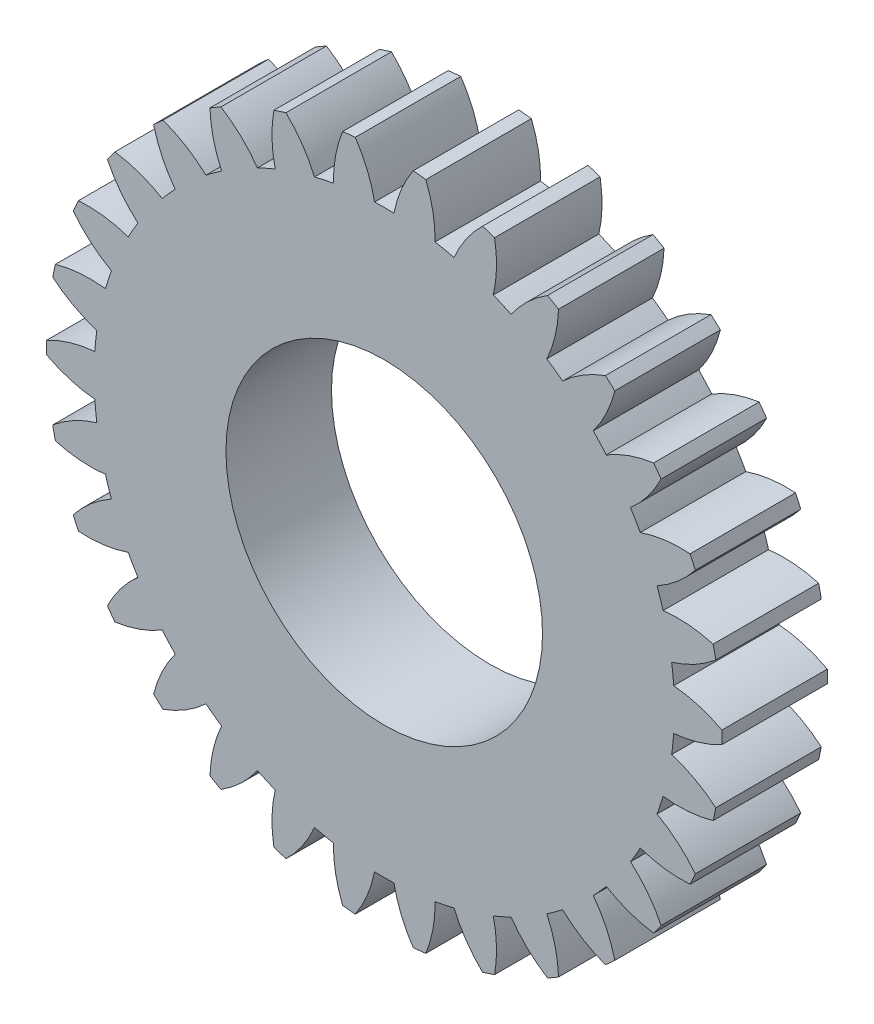
SolidWorks part; units mm, degrees
ref_plane "前基準面" through (0, 0, 0) normal (0, 0, 1) x (1, 0, 0)
ref_plane "上基準面" through (0, 0, 0) normal (0, 1, 0) x (1, 0, 0)
ref_plane "右基準面" through (0, 0, 0) normal (1, 0, 0) x (0, 0, -1)
sketch "草圖1" plane through (0, 0, 0) normal (0, 0, 1) x (1, 0, 0)
  circle A0 centre (0, 0) radius 15
  arc A240 (-31.9943, -0.6021) -> (-27.4291, -1.9593) centre (-26.3602, 9.993) ccw
  arc A241 (-27.4291, -1.9593) -> (-27.2371, -3.7863) centre (0, 0) ccw
  arc A242 (-27.2371, -3.7863) -> (-31.4204, -6.063) centre (-23.7065, -15.2552) ccw
  arc A243 (-31.4204, -6.063) -> (-31.17, -7.241) centre (0, 0) ccw
  arc A244 (-31.17, -7.241) -> (-26.4224, -7.6193) centre (-27.8618, 4.294) ccw
  arc A245 (-26.4224, -7.6193) -> (-25.8547, -9.3665) centre (0, 0) ccw
  arc A246 (-25.8547, -9.3665) -> (-29.4732, -12.4632) centre (-20.0167, -19.8507) ccw
  arc A247 (-29.4732, -12.4632) -> (-28.9834, -13.5633) centre (0, 0) ccw
  arc A248 (-28.9834, -13.5633) -> (-24.2608, -12.9463) centre (-28.1458, -1.5926) ccw
  arc A249 (-24.2608, -12.9463) -> (-23.3423, -14.5373) centre (0, 0) ccw
  arc A250 (-23.3423, -14.5373) -> (-26.2379, -18.3187) centre (-15.4521, -23.5786) ccw
  arc A251 (-26.2379, -18.3187) -> (-25.53, -19.2929) centre (0, 0) ccw
  arc A252 (-25.53, -19.2929) -> (-21.039, -17.7075) centre (-27.1996, -7.4096) ccw
  arc A253 (-21.039, -17.7075) -> (-19.8097, -19.0728) centre (0, 0) ccw
  arc A254 (-19.8097, -19.0728) -> (-21.8559, -23.3735) centre (-10.2122, -26.2761) ccw
  arc A255 (-21.8559, -23.3735) -> (-20.9609, -24.1793) centre (0, 0) ccw
  arc A256 (-20.9609, -24.1793) -> (-16.8976, -21.6948) centre (-25.0647, -12.9028) ccw
  arc A257 (-16.8976, -21.6948) -> (-15.4114, -22.7747) centre (0, 0) ccw
  arc A258 (-15.4114, -22.7747) -> (-16.5186, -27.4068) centre (-4.5259, -27.8251) ccw
  arc A259 (-16.5186, -27.4068) -> (-15.4757, -28.009) centre (0, 0) ccw
  arc A260 (-15.4757, -28.009) -> (-12.0177, -24.734) centre (-21.8343, -17.8321) ccw
  arc A261 (-12.0177, -24.734) -> (-10.3395, -25.4812) centre (0, 0) ccw
  arc A262 (-10.3395, -25.4812) -> (-10.4594, -30.2424) centre (1.3582, -28.158) ccw
  arc A263 (-10.4594, -30.2424) -> (-9.3141, -30.6145) centre (0, 0) ccw
  arc A264 (-9.3141, -30.6145) -> (-6.6127, -26.6921) centre (-17.6497, -21.982) ccw
  arc A265 (-6.6127, -26.6921) -> (-4.8157, -27.074) centre (0, 0) ccw
  arc A266 (-4.8157, -27.074) -> (-3.9431, -31.7561) centre (7.1829, -27.2603) ccw
  arc A267 (-3.9431, -31.7561) -> (-2.7455, -31.882) centre (0, 0) ccw
  arc A268 (-2.7455, -31.882) -> (-0.9186, -27.4837) centre (-12.6936, -25.1712) ccw
  arc A269 (-0.9186, -27.4837) -> (0.9186, -27.4837) centre (0, 0) ccw
  arc A270 (0.9186, -27.4837) -> (2.7455, -31.882) centre (12.6936, -25.1712) ccw
  arc A271 (2.7455, -31.882) -> (3.9431, -31.7561) centre (0, 0) ccw
  arc A272 (3.9431, -31.7561) -> (4.8157, -27.074) centre (-7.1829, -27.2603) ccw
  arc A273 (4.8157, -27.074) -> (6.6127, -26.6921) centre (0, 0) ccw
  arc A274 (6.6127, -26.6921) -> (9.3141, -30.6145) centre (17.6497, -21.982) ccw
  arc A275 (9.3141, -30.6145) -> (10.4594, -30.2424) centre (0, 0) ccw
  arc A276 (10.4594, -30.2424) -> (10.3395, -25.4812) centre (-1.3582, -28.158) ccw
  arc A277 (10.3395, -25.4812) -> (12.0177, -24.734) centre (0, 0) ccw
  arc A278 (12.0177, -24.734) -> (15.4757, -28.009) centre (21.8343, -17.8321) ccw
  arc A279 (15.4757, -28.009) -> (16.5186, -27.4068) centre (0, 0) ccw
  arc A280 (16.5186, -27.4068) -> (15.4114, -22.7747) centre (4.5259, -27.8251) ccw
  arc A281 (15.4114, -22.7747) -> (16.8976, -21.6948) centre (0, 0) ccw
  arc A282 (16.8976, -21.6948) -> (20.9609, -24.1793) centre (25.0647, -12.9028) ccw
  arc A283 (20.9609, -24.1793) -> (21.8559, -23.3735) centre (0, 0) ccw
  arc A284 (21.8559, -23.3735) -> (19.8097, -19.0728) centre (10.2122, -26.2761) ccw
  arc A285 (19.8097, -19.0728) -> (21.039, -17.7075) centre (0, 0) ccw
  arc A286 (21.039, -17.7075) -> (25.53, -19.2929) centre (27.1996, -7.4096) ccw
  arc A287 (25.53, -19.2929) -> (26.2379, -18.3187) centre (0, 0) ccw
  arc A288 (26.2379, -18.3187) -> (23.3423, -14.5373) centre (15.4521, -23.5786) ccw
  arc A289 (23.3423, -14.5373) -> (24.2608, -12.9463) centre (0, 0) ccw
  arc A290 (24.2608, -12.9463) -> (28.9834, -13.5633) centre (28.1458, -1.5926) ccw
  arc A291 (28.9834, -13.5633) -> (29.4732, -12.4632) centre (0, 0) ccw
  arc A292 (29.4732, -12.4632) -> (25.8547, -9.3665) centre (20.0167, -19.8507) ccw
  arc A293 (25.8547, -9.3665) -> (26.4224, -7.6193) centre (0, 0) ccw
  arc A294 (26.4224, -7.6193) -> (31.17, -7.241) centre (27.8618, 4.294) ccw
  arc A295 (31.17, -7.241) -> (31.4204, -6.063) centre (0, 0) ccw
  arc A296 (31.4204, -6.063) -> (27.2371, -3.7863) centre (23.7065, -15.2552) ccw
  arc A297 (27.2371, -3.7863) -> (27.4291, -1.9593) centre (0, 0) ccw
  arc A298 (27.4291, -1.9593) -> (31.9943, -0.6021) centre (26.3602, 9.993) ccw
  arc A299 (31.9943, -0.6021) -> (31.9943, 0.6021) centre (0, 0) ccw
  arc A300 (31.9943, 0.6021) -> (27.4291, 1.9593) centre (26.3602, -9.993) ccw
  arc A301 (27.4291, 1.9593) -> (27.2371, 3.7863) centre (0, 0) ccw
  arc A302 (27.2371, 3.7863) -> (31.4204, 6.063) centre (23.7065, 15.2552) ccw
  arc A303 (31.4204, 6.063) -> (31.17, 7.241) centre (0, 0) ccw
  arc A304 (31.17, 7.241) -> (26.4224, 7.6193) centre (27.8618, -4.294) ccw
  arc A305 (26.4224, 7.6193) -> (25.8547, 9.3665) centre (0, 0) ccw
  arc A306 (25.8547, 9.3665) -> (29.4732, 12.4632) centre (20.0167, 19.8507) ccw
  arc A307 (29.4732, 12.4632) -> (28.9834, 13.5633) centre (0, 0) ccw
  arc A308 (28.9834, 13.5633) -> (24.2608, 12.9463) centre (28.1458, 1.5926) ccw
  arc A309 (24.2608, 12.9463) -> (23.3423, 14.5373) centre (0, 0) ccw
  arc A310 (23.3423, 14.5373) -> (26.2379, 18.3187) centre (15.4521, 23.5786) ccw
  arc A311 (26.2379, 18.3187) -> (25.53, 19.2929) centre (0, 0) ccw
  arc A312 (25.53, 19.2929) -> (21.039, 17.7075) centre (27.1996, 7.4096) ccw
  arc A313 (21.039, 17.7075) -> (19.8097, 19.0728) centre (0, 0) ccw
  arc A314 (19.8097, 19.0728) -> (21.8559, 23.3735) centre (10.2122, 26.2761) ccw
  arc A315 (21.8559, 23.3735) -> (20.9609, 24.1793) centre (0, 0) ccw
  arc A316 (20.9609, 24.1793) -> (16.8976, 21.6948) centre (25.0647, 12.9028) ccw
  arc A317 (16.8976, 21.6948) -> (15.4114, 22.7747) centre (0, 0) ccw
  arc A318 (15.4114, 22.7747) -> (16.5186, 27.4068) centre (4.5259, 27.8251) ccw
  arc A319 (16.5186, 27.4068) -> (15.4757, 28.009) centre (0, 0) ccw
  arc A320 (15.4757, 28.009) -> (12.0177, 24.734) centre (21.8343, 17.8321) ccw
  arc A321 (12.0177, 24.734) -> (10.3395, 25.4812) centre (0, 0) ccw
  arc A322 (10.3395, 25.4812) -> (10.4594, 30.2424) centre (-1.3582, 28.158) ccw
  arc A323 (10.4594, 30.2424) -> (9.3141, 30.6145) centre (0, 0) ccw
  arc A324 (9.3141, 30.6145) -> (6.6127, 26.6921) centre (17.6497, 21.982) ccw
  arc A325 (6.6127, 26.6921) -> (4.8157, 27.074) centre (0, 0) ccw
  arc A326 (4.8157, 27.074) -> (3.9431, 31.7561) centre (-7.1829, 27.2603) ccw
  arc A327 (3.9431, 31.7561) -> (2.7455, 31.882) centre (0, 0) ccw
  arc A328 (2.7455, 31.882) -> (0.9186, 27.4837) centre (12.6936, 25.1712) ccw
  arc A329 (0.9186, 27.4837) -> (-0.9186, 27.4837) centre (0, 0) ccw
  arc A330 (-0.9186, 27.4837) -> (-2.7455, 31.882) centre (-12.6936, 25.1712) ccw
  arc A331 (-2.7455, 31.882) -> (-3.9431, 31.7561) centre (0, 0) ccw
  arc A332 (-3.9431, 31.7561) -> (-4.8157, 27.074) centre (7.1829, 27.2603) ccw
  arc A333 (-4.8157, 27.074) -> (-6.6127, 26.6921) centre (0, 0) ccw
  arc A334 (-6.6127, 26.6921) -> (-9.3141, 30.6145) centre (-17.6497, 21.982) ccw
  arc A335 (-9.3141, 30.6145) -> (-10.4594, 30.2424) centre (0, 0) ccw
  arc A336 (-10.4594, 30.2424) -> (-10.3395, 25.4812) centre (1.3582, 28.158) ccw
  arc A337 (-10.3395, 25.4812) -> (-12.0177, 24.734) centre (0, 0) ccw
  arc A338 (-12.0177, 24.734) -> (-15.4757, 28.009) centre (-21.8343, 17.8321) ccw
  arc A339 (-15.4757, 28.009) -> (-16.5186, 27.4068) centre (0, 0) ccw
  arc A340 (-16.5186, 27.4068) -> (-15.4114, 22.7747) centre (-4.5259, 27.8251) ccw
  arc A341 (-15.4114, 22.7747) -> (-16.8976, 21.6948) centre (0, 0) ccw
  arc A342 (-16.8976, 21.6948) -> (-20.9609, 24.1793) centre (-25.0647, 12.9028) ccw
  arc A343 (-20.9609, 24.1793) -> (-21.8559, 23.3735) centre (0, 0) ccw
  arc A344 (-21.8559, 23.3735) -> (-19.8097, 19.0728) centre (-10.2122, 26.2761) ccw
  arc A345 (-19.8097, 19.0728) -> (-21.039, 17.7075) centre (0, 0) ccw
  arc A346 (-21.039, 17.7075) -> (-25.53, 19.2929) centre (-27.1996, 7.4096) ccw
  arc A347 (-25.53, 19.2929) -> (-26.2379, 18.3187) centre (0, 0) ccw
  arc A348 (-26.2379, 18.3187) -> (-23.3423, 14.5373) centre (-15.4521, 23.5786) ccw
  arc A349 (-23.3423, 14.5373) -> (-24.2608, 12.9463) centre (0, 0) ccw
  arc A350 (-24.2608, 12.9463) -> (-28.9834, 13.5633) centre (-28.1458, 1.5926) ccw
  arc A351 (-28.9834, 13.5633) -> (-29.4732, 12.4632) centre (0, 0) ccw
  arc A352 (-29.4732, 12.4632) -> (-25.8547, 9.3665) centre (-20.0167, 19.8507) ccw
  arc A353 (-25.8547, 9.3665) -> (-26.4224, 7.6193) centre (0, 0) ccw
  arc A354 (-26.4224, 7.6193) -> (-31.17, 7.241) centre (-27.8618, -4.294) ccw
  arc A355 (-31.17, 7.241) -> (-31.4204, 6.063) centre (0, 0) ccw
  arc A356 (-31.4204, 6.063) -> (-27.2371, 3.7863) centre (-23.7065, 15.2552) ccw
  arc A357 (-27.2371, 3.7863) -> (-27.4291, 1.9593) centre (0, 0) ccw
  arc A358 (-27.4291, 1.9593) -> (-31.9943, 0.6021) centre (-26.3602, -9.993) ccw
  arc A359 (-31.9943, 0.6021) -> (-31.9943, -0.6021) centre (0, 0) ccw
extrude "填料-伸長1" add sketch "草圖1" along normal blind 10 contours A340 A341 A342 A343 A344 A345 A346 A347 A348 A349 A350 A351 A352 A353 A354 A355 A356 A357 A358 A359 A240 A241 A242 A243 A244 A245 A246 A247 A248 A249 A250 A251 A252 A253 A254 A255 A256 A257 A258 A259 A260 A261 A262 A263 A264 A265 A266 A267 A268 A269 A270 A271 A272 A273 A274 A275 A276 A277 A278 A279 A280 A281 A282 A283 A284 A285 A286 A287 A288 A289 A290 A291 A292 A293 A294 A295 A296 A297 A298 A299 A300 A301 A302 A303 A304 A305 A306 A307 A308 A309 A310 A311 A312 A313 A314 A315 A316 A317 A318 A319 A320 A321 A322 A323 A324 A325 A326 A327 A328 A329 A330 A331 A332 A333 A334 A335 A336 A337 A338 A339 | A0
